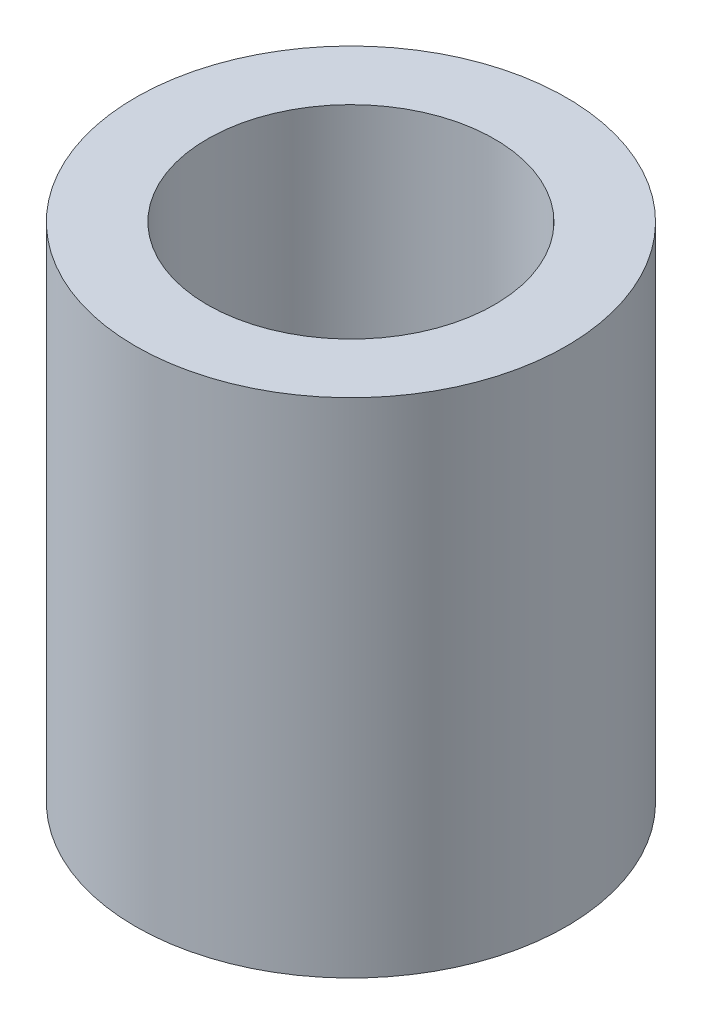
SolidWorks part; units mm, degrees
ref_plane "Front Plane" through (0, 0, 0) normal (0, 0, 1) x (1, 0, 0)
ref_plane "Top Plane" through (0, 0, 0) normal (0, 1, 0) x (1, 0, 0)
ref_plane "Right Plane" through (0, 0, 0) normal (1, 0, 0) x (0, 0, -1)
sketch "Sketch2" plane through (0, 0, 0) normal (0, 1, 0) x (1, 0, 0)
  circle A0 centre (0, 0) radius 2
  circle A1 centre (0, 0) radius 3
  dimension "D1" = 4
  dimension "D2" = 6
extrude "Boss-Extrude1" add sketch "Sketch2" along normal blind 7
